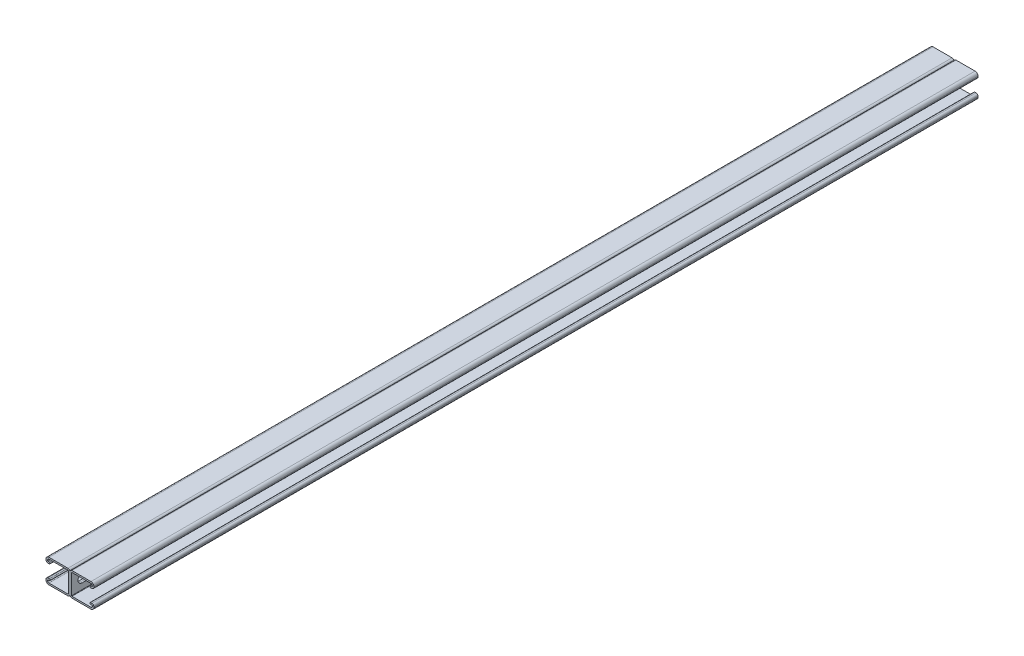
SolidWorks part; units mm, degrees
material "Galvanized Steel"
ref_plane "Front Plane" through (0, 0, 0) normal (0, 0, 1) x (1, 0, 0)
ref_plane "Top Plane" through (0, 0, 0) normal (0, 1, 0) x (1, 0, 0)
ref_plane "Right Plane" through (0, 0, 0) normal (1, 0, 0) x (0, 0, -1)
sketch "Sketch1" plane through (0, 0, 0) normal (0, 0, 1) x (1, 0, 0)
  line L0 (0, 0) -> (-41.275, 0) construction
  line L3 (-41.275, 20.6375) -> (0, 20.6375) construction
  line L4 (-41.275, 20.6375) -> (-41.275, -20.6375) construction
  line L5 (-41.275, -20.6375) -> (0, -20.6375) construction
  line L6 (0, 20.6375) -> (0, -20.6375) construction
  line L7 (-36.2267, 20.6375) -> (-3.4607, 20.6375)
  line L8 (0, 17.1767) -> (0, -17.1767)
  line L9 (-2.794, -17.1767) -> (-2.794, 17.1767)
  line L10 (-3.4607, 17.8435) -> (-36.2267, 17.8435)
  line L11 (-41.275, 15.5892) -> (-41.275, 14.5732)
  line L12 (-37.8142, 11.1125) -> (-35.5346, 11.1125)
  line L14 (-35.5346, 13.9065) -> (-37.8142, 13.9065)
  line L15 (-38.481, 14.5732) -> (-38.481, 15.5892)
  line L16 (-38.481, -14.5733) -> (-38.481, -15.5893)
  line L17 (-35.5346, -13.9065) -> (-37.8142, -13.9065)
  line L18 (-37.8142, -11.1125) -> (-35.5346, -11.1125)
  line L19 (-41.275, -15.5893) -> (-41.275, -14.5733)
  line L20 (-3.4607, -17.8435) -> (-36.2267, -17.8435)
  line L21 (-36.2267, -20.6375) -> (-3.4607, -20.6375)
  line L22 (-2.794, -20.6375) -> (-2.794, 20.6375) construction
  arc A1 (0, 17.1767) -> (-3.4607, 20.6375) centre (-3.4607, 17.1767) ccw
  arc A2 (-2.794, 17.1767) -> (-3.4607, 17.8435) centre (-3.4607, 17.1767) ccw
  arc A4 (-36.2267, 20.6375) -> (-41.275, 15.5892) centre (-36.2267, 15.5892) ccw
  arc A5 (-41.275, 14.5732) -> (-37.8142, 11.1125) centre (-37.8142, 14.5732) ccw
  arc A6 (-35.5346, 11.1125) -> (-35.5346, 13.9065) centre (-35.5346, 12.5095) ccw
  arc A7 (-37.8142, 13.9065) -> (-38.481, 14.5732) centre (-37.8142, 14.5732) cw
  arc A8 (-38.481, 15.5892) -> (-36.2267, 17.8435) centre (-36.2267, 15.5892) cw
  arc A9 (-38.481, -15.5893) -> (-36.2267, -17.8435) centre (-36.2267, -15.5893) ccw
  arc A10 (-37.8142, -13.9065) -> (-38.481, -14.5733) centre (-37.8142, -14.5733) ccw
  arc A11 (-35.5346, -11.1125) -> (-35.5346, -13.9065) centre (-35.5346, -12.5095) cw
  arc A12 (-41.275, -14.5733) -> (-37.8142, -11.1125) centre (-37.8142, -14.5733) cw
  arc A13 (-36.2267, -20.6375) -> (-41.275, -15.5893) centre (-36.2267, -15.5893) cw
  arc A14 (-2.794, -17.1767) -> (-3.4607, -17.8435) centre (-3.4607, -17.1767) cw
  arc A15 (0, -17.1767) -> (-3.4607, -20.6375) centre (-3.4607, -17.1767) cw
  point P24 (0, 20.6375)
  point P65 (-2.794, 0)
  dimension "D1" = 3.4608
  dimension "D2" = 5.0482
  dimension "D3" = 3.4608
  dimension "Ht." = 41.275
  dimension "Wd." = 41.275
  dimension "Thk." = 2.794
  dimension "D4" = 9.525
  dimension "D5" = 7.1374
extrude "Boss-Extrude1" add sketch "Sketch1" against normal blind 1524
sketch "Sketch3" plane through (0, 0, 0) normal (1, 0, 0) x (0, 0, -1)
  line L0 (0, 0) -> (1524, 0) construction
  point P2 (101.6, 0)
  point P3 (1422.4, 0)
  dimension "D1" = 101.6
  dimension "D2" = 101.6
  dimension "D3" = 1524
sketch "Sketch2" plane through (0, 0, 0) normal (1, 0, 0) x (0, 0, -1)
  line L0 (18.2562, 0) -> (32.5437, 0) construction
  line L1 (18.2562, 7.1437) -> (32.5437, 7.1437)
  line L2 (18.2562, -7.1437) -> (32.5437, -7.1437)
  line L3 (18.2562, 0) -> (0, 0) construction
  line L4 (25.4, 0) -> (76.2, 0) construction
  line L5 (0, -17.1767) -> (0, 17.1767) construction
  arc A0 (18.2562, 7.1437) -> (18.2562, -7.1437) centre (18.2562, 0) ccw
  arc A1 (32.5437, -7.1437) -> (32.5437, 7.1437) centre (32.5437, 0) ccw
  point P3 (25.4, 0)
  dimension "Hole to End" = 11.1125
  dimension "D2" = 25.4
extrude "Cut-Extrude1" cut sketch "Sketch2" against normal up to vertex (2.794 mm away) up to point (-2.794, 0, 0)
pattern_linear "LPattern1" count 30 spacing 50.8 along (0, 0, -1) of "Cut-Extrude1"
mirror "Mirror1" about plane through (0, 17.1767, -1524) normal (1, 0, 0) of bodies 116
equation "\"D1@LPattern1\" = \"Slot Ctr.@Sketch2\""
equation "\"Hole Count@LPattern1\" = \"Lg.@Boss-Extrude1\" / \"D1@LPattern1\""
equation "\"D3@Sketch3\" = \"Lg.@Boss-Extrude1\""
